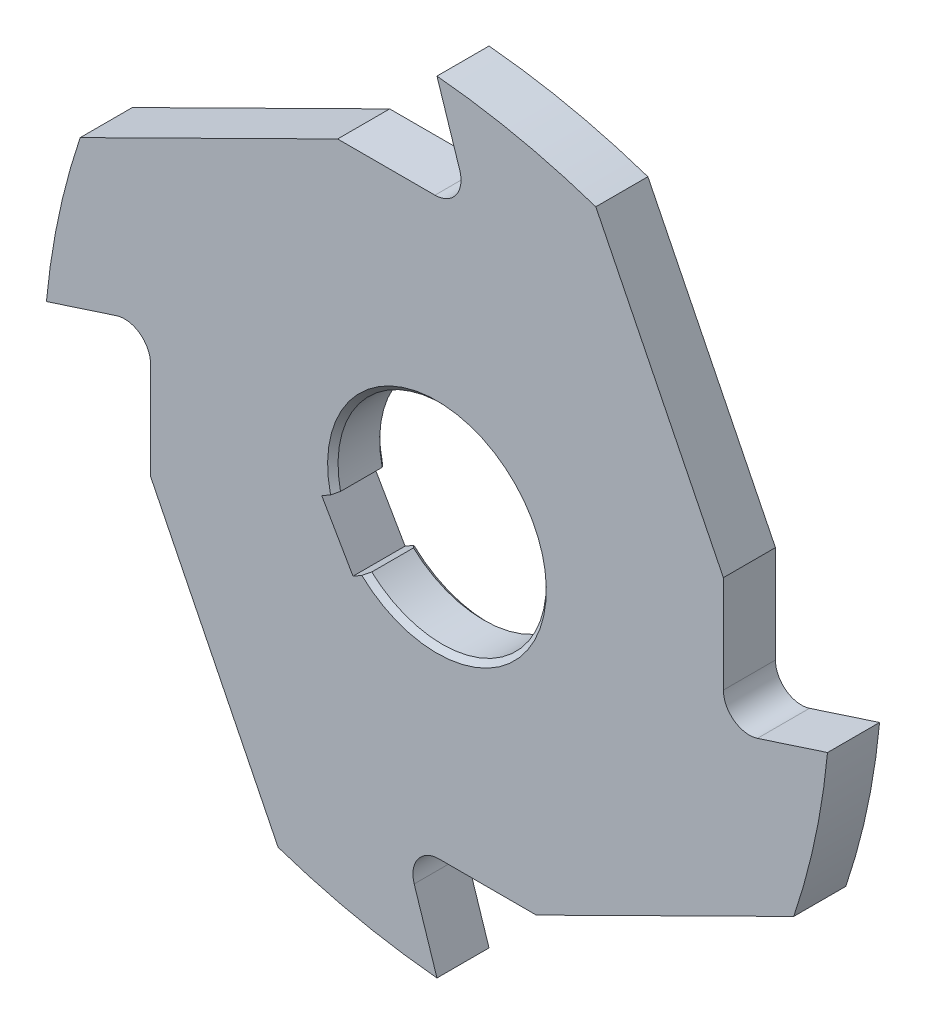
SolidWorks part; units mm, degrees
material "Cast Alloy Steel"
ref_plane "Front Plane" through (0, 0, 0) normal (0, 0, 1) x (1, 0, 0)
ref_plane "Top Plane" through (0, 0, 0) normal (0, 1, 0) x (1, 0, 0)
ref_plane "Right Plane" through (0, 0, 0) normal (1, 0, 0) x (0, 0, -1)
sketch "Sketch1" plane through (0, 0, 0) normal (0, 0, 1) x (1, 0, 0)
  line L0 (-55, 0) -> (55, 0) construction
  line L1 (0, -75) -> (0, 75) construction
  line L2 (-52.0911, 75) -> (52.0911, 75) construction
  line L3 (-52.0911, 55) -> (-50.9902, 55) construction
  line L4 (-13.5227, -14.7355) -> (-16.1208, -16.2355)
  line L5 (-16.1208, -16.2355) -> (-22.1208, -5.8432)
  line L6 (0, 75) -> (30.5052, 68.5159) construction
  line L7 (-19.5227, -4.3432) -> (-22.1208, -5.8432)
  line L8 (0, 55) -> (5, 55) construction
  line L9 (-0.3835, 55) -> (-20, 55)
  line L10 (0, 75) -> (4.3718, 61.5451)
  line L11 (55, -75) -> (55, 75) construction
  line L12 (-55, -75) -> (-55, 75) construction
  line L13 (6, 19.0788) -> (104, 19.0788) construction
  line L14 (55, 0) -> (55, 19.0788)
  line L15 (55, 19.0788) -> (30.5052, 68.5159)
  line L16 (5, -75) -> (5, 75) construction
  line L17 (-20, -75) -> (-20, 75) construction
  line L18 (-20, 55) -> (52.0911, 55) construction
  line L19 (-52.0911, 55) -> (52.0911, 55) construction
  line L20 (55, 0.3835) -> (55, 20)
  line L21 (75, 0) -> (61.5451, -4.3718)
  line L22 (19.0788, -55) -> (68.5159, -30.5052)
  line L23 (0, -55) -> (19.0788, -55)
  line L24 (0.3835, -55) -> (20, -55)
  line L25 (0, -75) -> (-4.3718, -61.5451)
  line L26 (-55, -19.0788) -> (-30.5052, -68.5159)
  line L27 (-55, 0) -> (-55, -19.0788)
  line L28 (-55, -0.3835) -> (-55, -20)
  line L29 (-75, 0) -> (-61.5451, 4.3718)
  line L30 (-19.0788, 55) -> (-68.5159, 30.5052)
  line L31 (0, 55) -> (-19.0788, 55)
  circle A0 centre (0, 0) radius 75
  arc A1 (6, 19.0788) -> (-19.5227, -4.3432) centre (0, 0) ccw
  arc A2 (-0.3835, 55) -> (4.3718, 61.5451) centre (-0.3835, 60) ccw
  arc A3 (0, 75) -> (30.5052, 68.5159) centre (-12.6276, -59.4081) cw
  arc A4 (55, 0.3835) -> (61.5451, -4.3718) centre (60, 0.3835) ccw
  arc A5 (75, 0) -> (68.5159, -30.5052) centre (-59.4081, 12.6276) cw
  arc A6 (0.3835, -55) -> (-4.3718, -61.5451) centre (0.3835, -60) ccw
  arc A7 (0, -75) -> (-30.5052, -68.5159) centre (12.6276, 59.4081) cw
  arc A8 (-55, -0.3835) -> (-61.5451, 4.3718) centre (-60, -0.3835) ccw
  arc A9 (-75, 0) -> (-68.5159, 30.5052) centre (59.4081, -12.6276) cw
  arc A10 (13.5227, -14.7355) -> (6, 19.0788) centre (0, 0) ccw
  arc A11 (-13.5227, -14.7355) -> (13.5227, -14.7355) centre (0, 0) ccw
  point P4 (0, 0)
  point P7 (0, 0)
  point P15 (0, 0)
  point P18 (0, 75)
  point P19 (0, 0)
  point P67 (0, 0)
  point P75 (0, 0)
  point P77 (0, 0)
  dimension "D1" = 150
  dimension "D2" = 40
  dimension "D7" = 5
  dimension "D12" = 135
  dimension "D13" = 5
  dimension "D3" = 12
  dimension "D4" = 3
  dimension "D5" = 6
  dimension "D6" = 20
  dimension "D8" = 60
  dimension "D9" = 18
  dimension "D10" = 55
  dimension "D16" = 30
  dimension "D17" = 60
  dimension "D18" = 4.3432
  dimension "D11" = 55
  dimension "D14" = 25
  dimension "D15" = 4
extrude "Boss-Extrude1" add sketch "Sketch1" against normal blind 10
chamfer "Chamfer1" distance 1 angle 45 2 edges at (17.3205, 10, -10) (17.3205, 10, 0)
